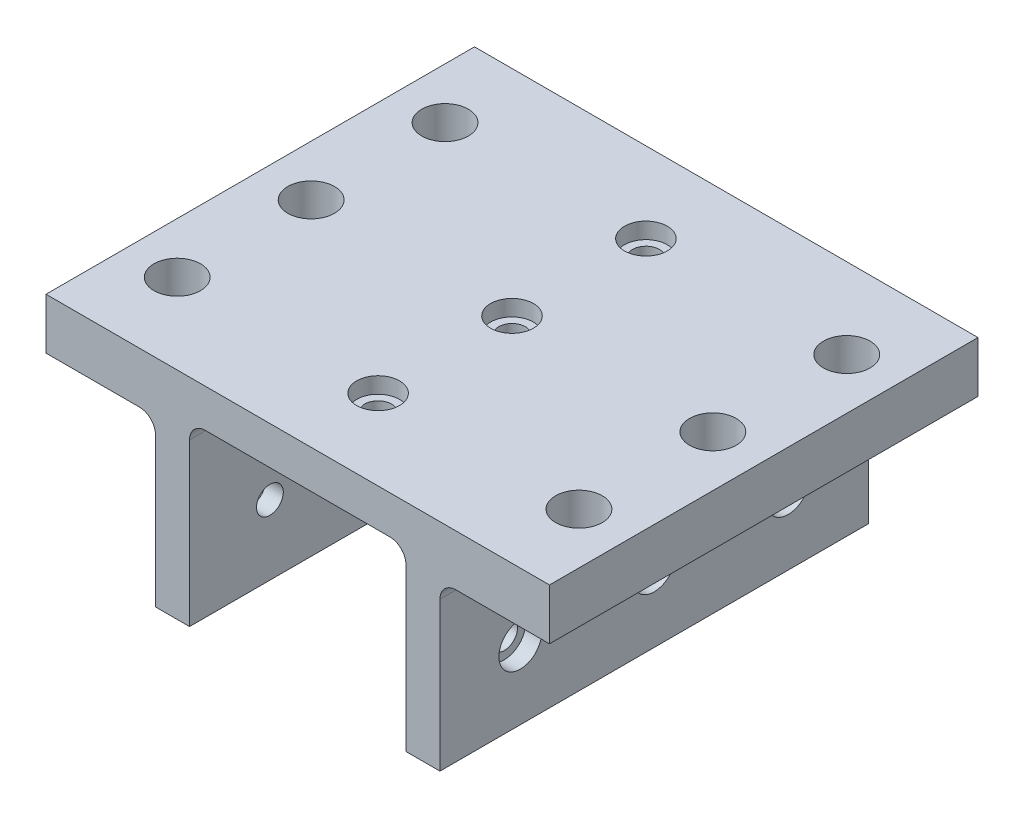
SolidWorks part; units mm, degrees
ref_plane "Front Plane" through (0, 0, 0) normal (0, 0, 1) x (1, 0, 0)
ref_plane "Top Plane" through (0, 0, 0) normal (0, 1, 0) x (1, 0, 0)
ref_plane "Right Plane" through (0, 0, 0) normal (1, 0, 0) x (0, 0, -1)
sketch "Sketch2" plane through (0, 0, 0) normal (0, 0, 1) x (1, 0, 0)
  line L0 (59.4222, 153.6369) -> (153.4222, 153.6369)
  line L1 (126.6222, 113.2999) -> (132.9722, 113.2999)
  line L2 (59.4222, 144.1119) -> (76.8722, 144.1119)
  line L3 (59.4222, 144.1119) -> (59.4222, 153.6369)
  line L4 (126.6222, 138.3499) -> (126.6222, 113.2499)
  line L5 (86.2222, 113.2499) -> (86.2222, 138.3499)
  line L6 (79.8722, 113.2999) -> (79.8722, 141.1119)
  line L7 (86.2222, 113.2999) -> (86.2222, 143.4999)
  line L8 (126.6222, 113.2999) -> (126.6222, 143.4999)
  line L9 (79.8722, 113.2999) -> (86.2222, 113.2999)
  line L10 (94.3722, 146.4999) -> (118.4722, 146.4999)
  line L11 (89.2222, 146.4999) -> (123.6222, 146.4999)
  line L12 (132.9722, 113.2999) -> (132.9722, 141.1119)
  line L13 (135.9722, 144.1119) -> (153.4222, 144.1119)
  line L14 (153.4222, 144.1119) -> (153.4222, 153.6369)
  arc A0 (79.8722, 141.1119) -> (76.8722, 144.1119) centre (76.8722, 141.1119) ccw
  arc A1 (89.2222, 146.4999) -> (86.2222, 143.4999) centre (89.2222, 143.4999) ccw
  arc A2 (126.6222, 143.4999) -> (123.6222, 146.4999) centre (123.6222, 143.4999) ccw
  arc A3 (135.9722, 144.1119) -> (132.9722, 141.1119) centre (135.9722, 141.1119) ccw
extrude "Extrude1" add sketch "Sketch2" along normal blind 80
sketch "Sketch3" plane through (0, 153.6369, 0) normal (0, 1, 0) x (-1, 0, 0)
  line L0 (-59.4222, 80) -> (-153.4222, 80) construction
  line L1 (-59.4222, 80) -> (-59.4222, 0) construction
  line L2 (-68.9222, 65) -> (-68.9222, 4.8475) construction
  line L4 (-106.4222, 80) -> (-106.4222, 0) construction
  line L5 (-59.4222, 0) -> (-153.4222, 0) construction
  point P0 (-68.9222, 65)
  point P1 (-68.9222, 40)
  point P2 (-68.9222, 15)
  point P13 (-143.9222, 15)
  point P14 (-143.9222, 40)
  point P16 (-143.9222, 65)
  point P17 (-106.4222, 65)
  point P18 (-106.4222, 40)
  point P19 (-106.4222, 15)
  dimension "D1" = 15
  dimension "D2" = 9.5
  dimension "D3" = 25
  dimension "D4" = 25
hole_wizard "M8.7 (8.7) Diameter Hole1" positions "3DSketch1" profile "Sketch4" hole size "M8.7" standard "DIN" end condition through all
sketch3d "3DSketch1"
  point P0 (68.9222, 153.6369, 65)
  point P2 (68.9222, 153.6369, 40)
  point P4 (68.9222, 153.6369, 15)
  point P6 (143.9222, 153.6369, 15)
  point P8 (143.9222, 153.6369, 40)
  point P10 (143.9222, 153.6369, 65)
sketch "Sketch4" plane through (68.9222, 153.6369, 65) normal (1, 0, 0) x (0, 0, 1)
  line L0 (0, 0) -> (0, 40.337)
  line L1 (0, 40.337) -> (4.35, 40.337)
  line L2 (4.35, 40.337) -> (4.35, 0)
  line L5 (4.35, 0) -> (0, 0)
  line L11 (0, -6.35) -> (0, 107.95) construction
  dimension "Thru Hole Dia." = 8.7
  dimension "Thru Hole Depth" = 40.337
hole_wizard "Hole1" positions "3DSketch2" profile "Sketch5" legacy end condition through all
sketch3d "3DSketch2"
  point P0 (106.4222, 153.6369, 65)
  point P2 (106.4222, 153.6369, 40)
  point P4 (106.4222, 153.6369, 15)
sketch "Sketch5" plane through (106.4222, 153.6369, 65) normal (1, 0, 0) x (0, 0, 1)
  line L0 (0, 0) -> (0, 40.337)
  line L1 (0, 40.337) -> (2.5, 40.337)
  line L2 (2.5, 40.337) -> (2.5, 3)
  line L3 (2.5, 3) -> (4, 3)
  line L4 (4, 3) -> (4, 0)
  line L5 (4, 0) -> (0, 0)
  line L6 (0, 110) -> (0, -10) construction
  dimension "Diameter" = 5
  dimension "Depth" = 40.337
  dimension "C-Bore Diameter" = 8
  dimension "C-Bore Depth" = 3
sketch "Sketch6" plane through (132.9722, 0, 0) normal (1, 0, 0) x (0, 0, -1)
  line L0 (-80, 153.6369) -> (0, 153.6369) construction
  line L1 (-80, 113.2999) -> (-80, 141.1119) construction
  line L2 (-65, 126.2969) -> (-8.0106, 126.2969) construction
  point P0 (-65, 126.2969)
  point P7 (-40, 126.2969)
  point P8 (-15, 126.2969)
  dimension "D1" = 27.34
  dimension "D2" = 15
  dimension "D3" = 25
  dimension "D4" = 25
hole_wizard "Hole2" positions "3DSketch3" profile "Sketch7" legacy
sketch3d "3DSketch3"
  point P0 (132.9722, 126.2969, 65)
  point P2 (132.9722, 126.2969, 40)
  point P4 (132.9722, 126.2969, 15)
sketch "Sketch7" plane through (132.9722, 126.2969, 65) normal (0, 1, 0) x (0, 0, -1)
  line L0 (0, 0) -> (0, 7)
  line L1 (0, 7) -> (2.5, 7)
  line L2 (2.5, 7) -> (2.5, 3)
  line L3 (2.5, 3) -> (4, 3)
  line L4 (4, 3) -> (4, 0)
  line L5 (4, 0) -> (0, 0)
  line L6 (0, 110) -> (0, -10) construction
  dimension "Diameter" = 5
  dimension "Depth" = 7
  dimension "C-Bore Diameter" = 8
  dimension "C-Bore Depth" = 3
ref_plane "MirrorPlane" through (106.4222, 0, 0) normal (-1, 0, 0) x (0, 0, 1)
mirror "Mirror1" about plane through (106.4222, 0, 0) normal (-1, 0, 0) of "Hole2"
